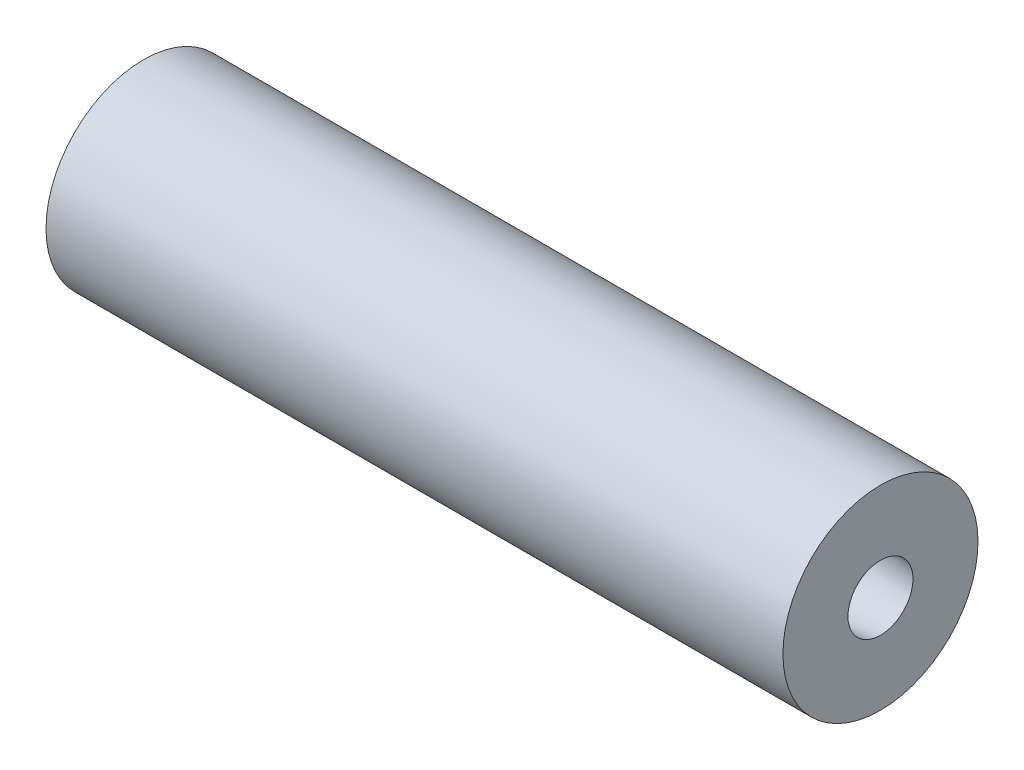
SolidWorks part; units mm, degrees
ref_plane "Спереди" through (0, 0, 0) normal (0, 0, 1) x (1, 0, 0)
ref_plane "Сверху" through (0, 0, 0) normal (0, 1, 0) x (1, 0, 0)
ref_plane "Справа" through (0, 0, 0) normal (1, 0, 0) x (0, 0, -1)
sketch "Эскиз1" plane through (0, 0, 0) normal (0, 0, 1) x (1, 0, 0)
  line L0 (0, 0) -> (16.7172, 0) construction
  line L1 (0, 9) -> (68, 9)
  line L2 (68, 9) -> (68, 3)
  line L3 (68, 3) -> (0, 8)
  line L4 (0, 8) -> (0, 9)
  line L5 (0, 0) -> (0, 24.6569) construction
  dimension "D1" = 18
  dimension "D2" = 68
  dimension "D3" = 1
  dimension "D4" = 6
revolve "Повернуть1" add sketch "Эскиз1" angle 360 about L0
